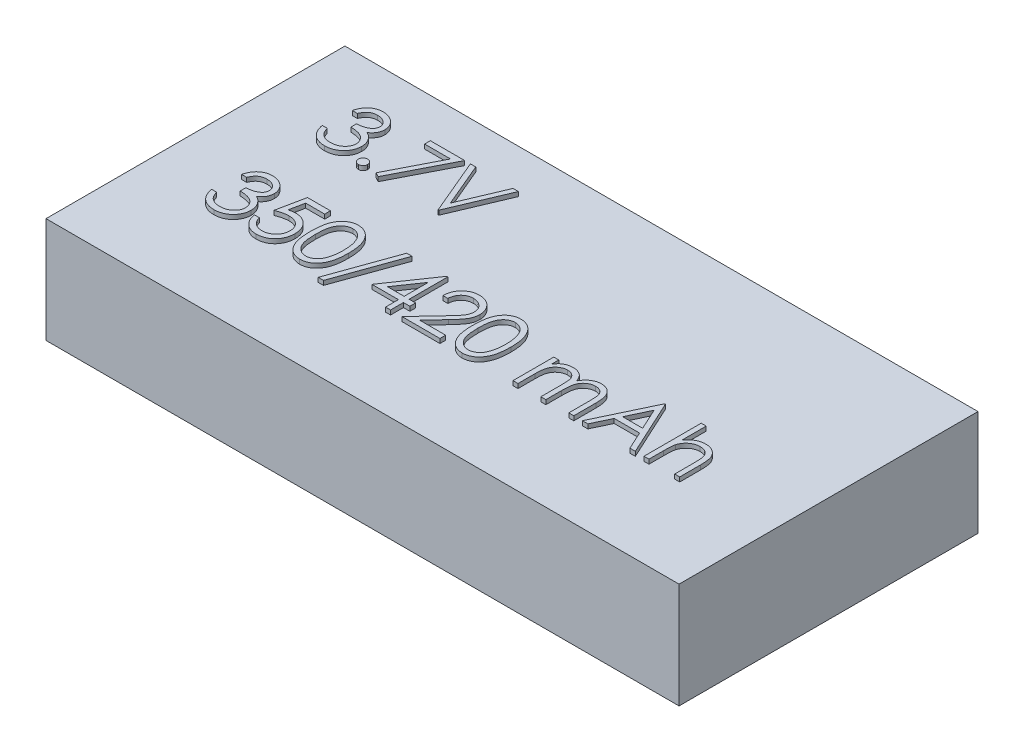
SolidWorks part; units mm, degrees
ref_plane "Front Plane" through (0, 0, 0) normal (0, 0, 1) x (1, 0, 0)
ref_plane "Top Plane" through (0, 0, 0) normal (0, 1, 0) x (1, 0, 0)
ref_plane "Right Plane" through (0, 0, 0) normal (1, 0, 0) x (0, 0, -1)
sketch "Sketch1" plane through (0, 0, 0) normal (0, 1, 0) x (1, 0, 0)
  line L1 (18, -8.5) -> (-18, -8.5)
  line L2 (18, -8.5) -> (18, 8.5)
  line L3 (18, 8.5) -> (-18, 8.5)
  line L4 (-18, -8.5) -> (-18, 8.5)
  line L5 (18, -8.5) -> (-18, 8.5) construction
  line L6 (18, 8.5) -> (-18, -8.5) construction
  point P0 (0, 0)
  dimension "D1" = 36
  dimension "D2" = 17
extrude "Boss-Extrude1" add sketch "Sketch1" along normal blind 6
sketch "Sketch2" plane through (0, 6, 0) normal (0, 1, 0) x (1, 0, 0)
  text T0 "3.7V\r\n350/420 mAh"
extrude "Boss-Extrude2" add sketch "Sketch2" along normal blind 0.25
